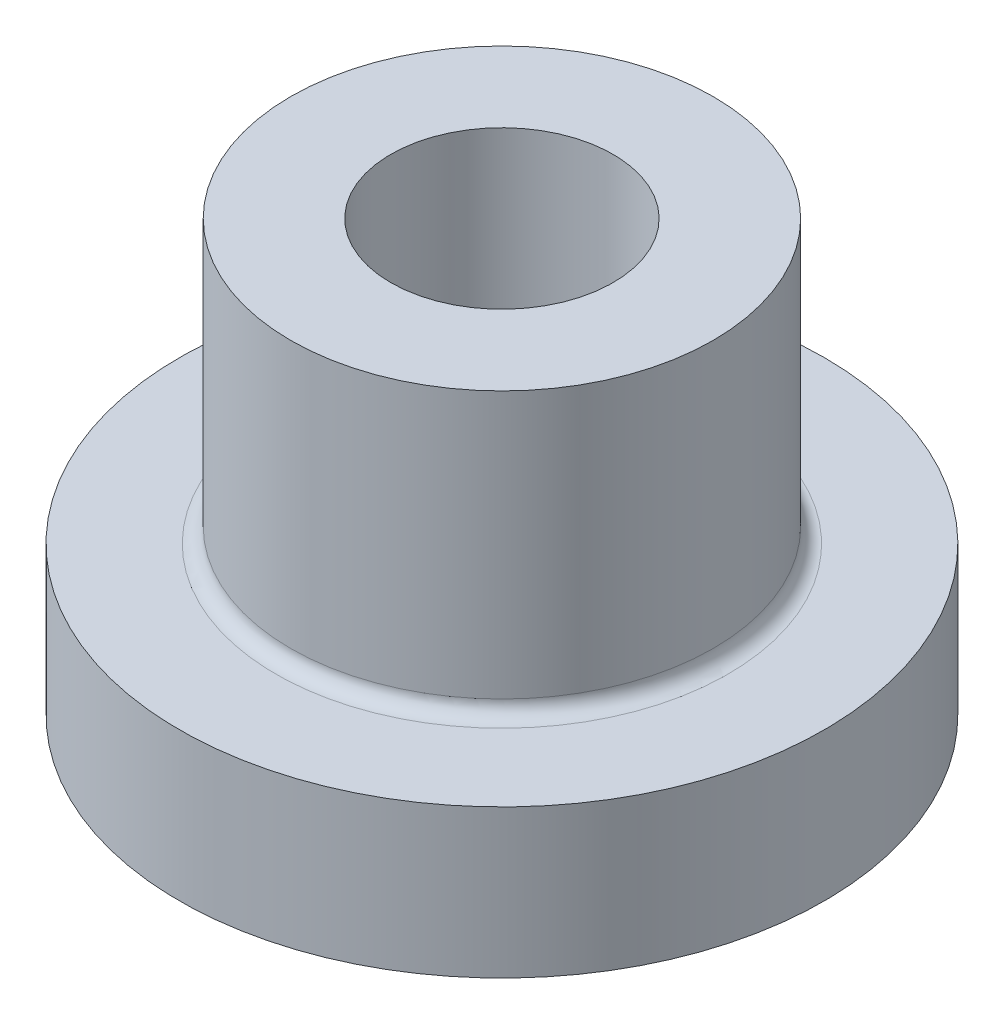
SolidWorks part; units mm, degrees
ref_plane "Front Plane" through (0, 0, 0) normal (0, 0, 1) x (1, 0, 0)
ref_plane "Top Plane" through (0, 0, 0) normal (0, 1, 0) x (1, 0, 0)
ref_plane "Right Plane" through (0, 0, 0) normal (1, 0, 0) x (0, 0, -1)
sketch "Sketch1" plane through (0, 0, 0) normal (0, 1, 0) x (1, 0, 0)
  circle A0 centre (0, 0) radius 2.85
  dimension "D1" = 5.7
extrude "Boss-Extrude1" add sketch "Sketch1" along normal blind 4.2
shell "Shell1" thickness 1.35
sketch "Sketch2" plane through (0, 0, 0) normal (0, -1, 0) x (1, 0, 0)
  circle A0 centre (0, 0) radius 2.85 construction
  circle A1 centre (0, 0) radius 2.85
  circle A2 centre (0, 0) radius 4.35
  dimension "D1" = 1.5
extrude "Boss-Extrude2" add sketch "Sketch2" along normal blind 1.6 and the other way blind 0.4
fillet "Fillet4" radius 0.2 2 edges at (0, 0, 2.85) (0, 0.4, -2.85)
